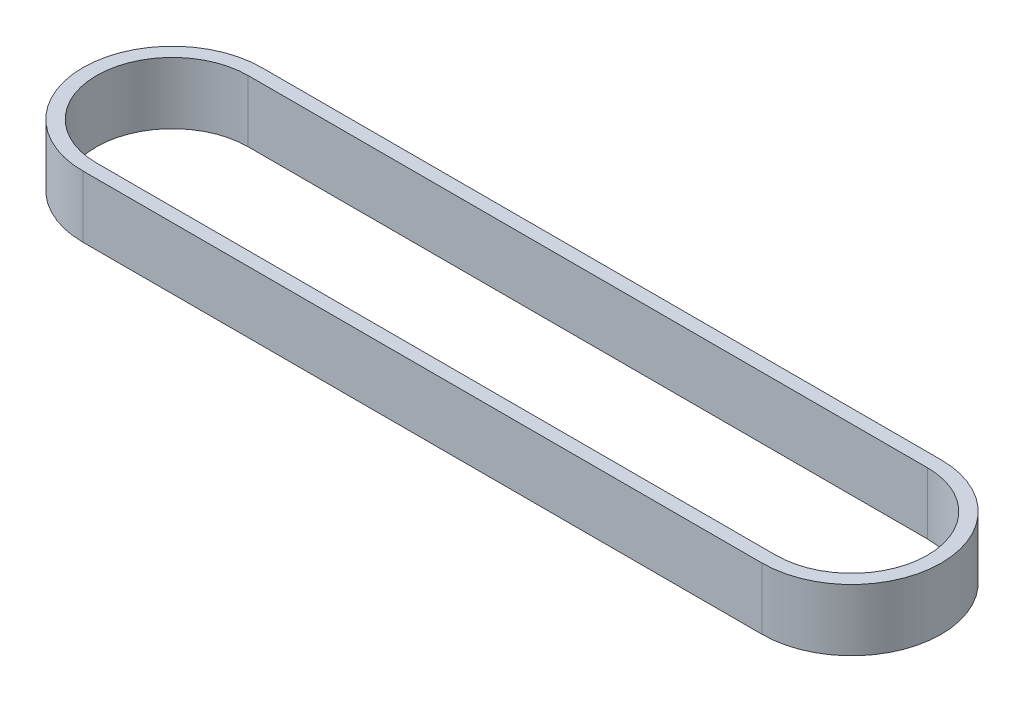
SolidWorks part; units mm, degrees
ref_plane "Front Plane" through (0, 0, 0) normal (0, 0, 1) x (1, 0, 0)
ref_plane "Top Plane" through (0, 0, 0) normal (0, 1, 0) x (1, 0, 0)
ref_plane "Right Plane" through (0, 0, 0) normal (1, 0, 0) x (0, 0, -1)
sketch "Sketch1" plane through (0, 0, 0) normal (0, 1, 0) x (1, 0, 0)
  line L0 (49.53, 0) -> (-49.53, 0) construction
  line L1 (49.53, -11.049) -> (-49.53, -11.049)
  line L2 (49.53, 11.049) -> (-49.53, 11.049)
  line L3 (49.53, 0) -> (-49.53, 0) construction
  line L4 (49.53, -13.049) -> (-49.53, -13.049)
  line L5 (49.53, 13.049) -> (-49.53, 13.049)
  arc A0 (49.53, -11.049) -> (49.53, 11.049) centre (49.53, 0) ccw
  arc A1 (-49.53, 11.049) -> (-49.53, -11.049) centre (-49.53, 0) ccw
  arc A2 (49.53, -13.049) -> (49.53, 13.049) centre (49.53, 0) ccw
  arc A3 (-49.53, 13.049) -> (-49.53, -13.049) centre (-49.53, 0) ccw
  point P2 (0, 0)
  point P9 (0, 0)
  point P15 (0, 0)
  dimension "D2" = 11.049
  dimension "D1" = 99.06
  dimension "D3" = 2
extrude "Boss-Extrude1" add sketch "Sketch1" along normal blind 9
